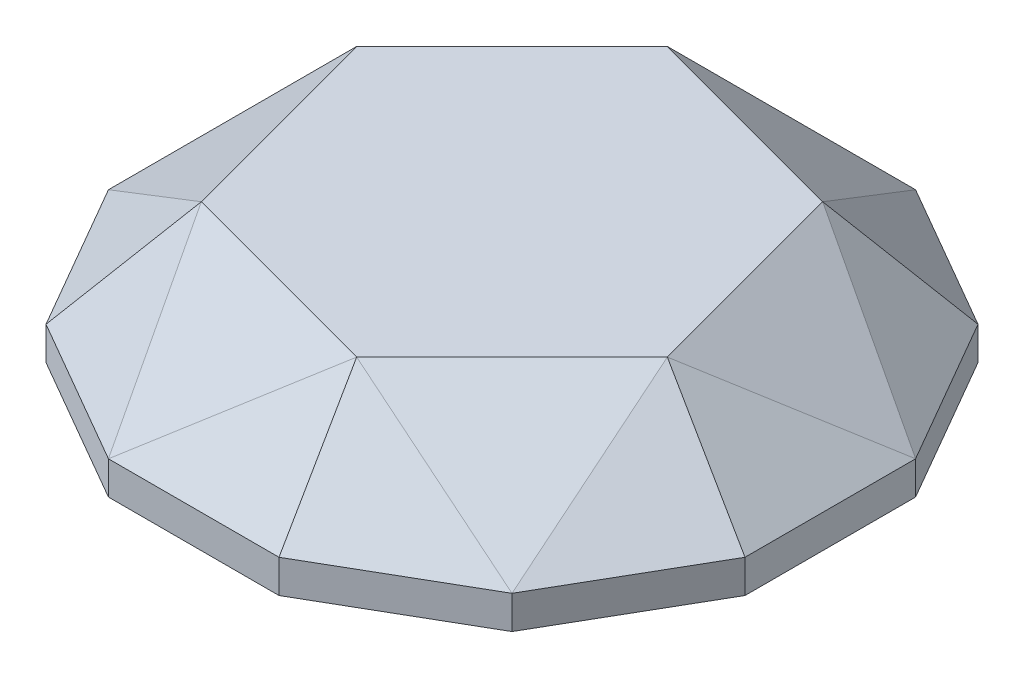
SolidWorks part; units mm, degrees
ref_plane "Front Plane" through (0, 0, 0) normal (0, 0, 1) x (1, 0, 0)
ref_plane "Top Plane" through (0, 0, 0) normal (0, 1, 0) x (1, 0, 0)
ref_plane "Right Plane" through (0, 0, 0) normal (1, 0, 0) x (0, 0, -1)
sketch "Sketch1" plane through (0, 0, 0) normal (0, 1, 0) x (1, 0, 0)
  circle A0 centre (0, 0) radius 27.94
  circle A1 centre (0, 0) radius 30.48
sketch "Sketch2" plane through (0, 0, 0) normal (0, 1, 0) x (1, 0, 0)
  line L1 (-11.1565, -11.1565) -> (-4.0835, -15.24)
  line L2 (-4.0835, -15.24) -> (4.0835, -15.24)
  line L3 (4.0835, -15.24) -> (11.1565, -11.1565)
  line L4 (11.1565, -11.1565) -> (15.24, -4.0835)
  line L5 (15.24, -4.0835) -> (15.24, 4.0835)
  line L6 (15.24, 4.0835) -> (11.1565, 11.1565)
  line L7 (11.1565, 11.1565) -> (4.0835, 15.24)
  line L8 (4.0835, 15.24) -> (-4.0835, 15.24)
  line L9 (-4.0835, 15.24) -> (-11.1565, 11.1565)
  line L10 (-11.1565, 11.1565) -> (-15.24, 4.0835)
  line L11 (-15.24, 4.0835) -> (-15.24, -4.0835)
  line L12 (-15.24, -4.0835) -> (-11.1565, -11.1565)
  circle A0 centre (0, 0) radius 15.24 construction
  dimension "D1" = 30.48
extrude "Boss-Extrude2" add sketch "Sketch2" along normal blind 5.08 draft 45 contours L11 L12 L1 L2 L3 L4 L5 L6 L7 L8 L9 L10
ref_plane "Plane4" through (-1.4996, 7.6056, 5.5965) normal (0.1568, -0.7955, -0.5853) x (-0.9876, -0.1239, -0.0963)
sketch "Sketch3" plane through (-1.4996, 7.6056, 5.5965) normal (0.1568, -0.7955, -0.5853) x (-0.9876, -0.1239, -0.0963)
  line L0 (-4.2964, -5.1546) -> (6, -3.0048)
  line L1 (6, -3.0048) -> (2.5652, -12.2857)
  line L2 (2.5652, -12.2857) -> (-4.2964, -5.1546)
extrude "Cut-Extrude1" cut sketch "Sketch3" against normal through all
sketch3d "3DSketch1"
  line L0 (0, 0, 0) -> (0, 8.2426, 0) construction
pattern_circular "CirPattern1" count 6 over 360 about axis through (0, 0, 0) along (0, 1, 0) of "Cut-Extrude1"
sketch "Sketch5" plane through (0, 0, 0) normal (0, -1, 0) x (1, 0, 0)
  line L1 (13.9334, -3.8773) -> (14.0053, 3.6089)
  line L2 (14.0053, 3.6089) -> (10.3245, 10.128)
  line L3 (10.3245, 10.128) -> (3.8773, 13.9334)
  line L4 (3.8773, 13.9334) -> (-3.6089, 14.0053)
  line L5 (-3.6089, 14.0053) -> (-10.128, 10.3245)
  line L6 (-10.128, 10.3245) -> (-13.9334, 3.8773)
  line L7 (-13.9334, 3.8773) -> (-14.0053, -3.6089)
  line L8 (-14.0053, -3.6089) -> (-10.3245, -10.128)
  line L9 (-10.3245, -10.128) -> (-3.8773, -13.9334)
  line L10 (-3.8773, -13.9334) -> (3.6089, -14.0053)
  line L11 (3.6089, -14.0053) -> (10.128, -10.3245)
  line L12 (10.128, -10.3245) -> (13.9334, -3.8773)
  circle A0 centre (0, 0) radius 13.97 construction
extrude "Cut-Extrude2" cut sketch "Sketch5" against normal blind 4.572 draft 50
sketch "Sketch8" plane through (0, 0, 0) normal (0, -1, 0) x (1, 0, 0)
  line L12 (-15.24, -4.0835) -> (-11.1565, -11.1565)
  line L13 (-11.1565, -11.1565) -> (-4.0835, -15.24)
  line L14 (-4.0835, -15.24) -> (4.0835, -15.24)
  line L15 (4.0835, -15.24) -> (11.1565, -11.1565)
  line L16 (11.1565, -11.1565) -> (15.24, -4.0835)
  line L17 (15.24, -4.0835) -> (15.24, 4.0835)
  line L18 (15.24, 4.0835) -> (11.1565, 11.1565)
  line L19 (11.1565, 11.1565) -> (4.0835, 15.24)
  line L20 (4.0835, 15.24) -> (-4.0835, 15.24)
  line L21 (-4.0835, 15.24) -> (-11.1565, 11.1565)
  line L22 (-11.1565, 11.1565) -> (-15.24, 4.0835)
  line L23 (-15.24, 4.0835) -> (-15.24, -4.0835)
  line L24 (-15.24, -4.0835) -> (-11.1565, -11.1565)
  line L25 (-11.1565, -11.1565) -> (-4.0835, -15.24)
  line L26 (-4.0835, -15.24) -> (4.0835, -15.24)
  line L27 (4.0835, -15.24) -> (11.1565, -11.1565)
  line L28 (11.1565, -11.1565) -> (15.24, -4.0835)
  line L29 (15.24, -4.0835) -> (15.24, 4.0835)
  line L30 (15.24, 4.0835) -> (11.1565, 11.1565)
  line L31 (11.1565, 11.1565) -> (4.0835, 15.24)
  line L32 (4.0835, 15.24) -> (-4.0835, 15.24)
  line L33 (-4.0835, 15.24) -> (-11.1565, 11.1565)
  line L34 (-11.1565, 11.1565) -> (-15.24, 4.0835)
  line L35 (-15.24, 4.0835) -> (-15.24, -4.0835)
  line L36 (-10.128, 10.3245) -> (-13.9334, 3.8773) construction
  line L37 (-10.128, 10.3245) -> (-13.9334, 3.8773)
  line L38 (10.3245, 10.128) -> (3.8773, 13.9334) construction
  line L39 (14.0053, 3.6089) -> (10.3245, 10.128) construction
  line L40 (13.9334, -3.8773) -> (14.0053, 3.6089) construction
  line L41 (10.128, -10.3245) -> (13.9334, -3.8773) construction
  line L42 (3.6089, -14.0053) -> (10.128, -10.3245) construction
  line L43 (-3.8773, -13.9334) -> (3.6089, -14.0053) construction
  line L44 (-10.3245, -10.128) -> (-3.8773, -13.9334) construction
  line L45 (-14.0053, -3.6089) -> (-10.3245, -10.128) construction
  line L46 (-13.9334, 3.8773) -> (-14.0053, -3.6089) construction
  line L47 (-3.6089, 14.0053) -> (-10.128, 10.3245) construction
  line L48 (3.8773, 13.9334) -> (-3.6089, 14.0053) construction
  line L49 (10.3245, 10.128) -> (3.8773, 13.9334)
  line L50 (14.0053, 3.6089) -> (10.3245, 10.128)
  line L51 (13.9334, -3.8773) -> (14.0053, 3.6089)
  line L52 (10.128, -10.3245) -> (13.9334, -3.8773)
  line L53 (3.6089, -14.0053) -> (10.128, -10.3245)
  line L54 (-3.8773, -13.9334) -> (3.6089, -14.0053)
  line L55 (-10.3245, -10.128) -> (-3.8773, -13.9334)
  line L56 (-14.0053, -3.6089) -> (-10.3245, -10.128)
  line L57 (-13.9334, 3.8773) -> (-14.0053, -3.6089)
  line L58 (-3.6089, 14.0053) -> (-10.128, 10.3245)
  line L59 (3.8773, 13.9334) -> (-3.6089, 14.0053)
  dimension "D1" = 0
extrude "Boss-Extrude3" add sketch "Sketch8" along normal blind 1.5875
